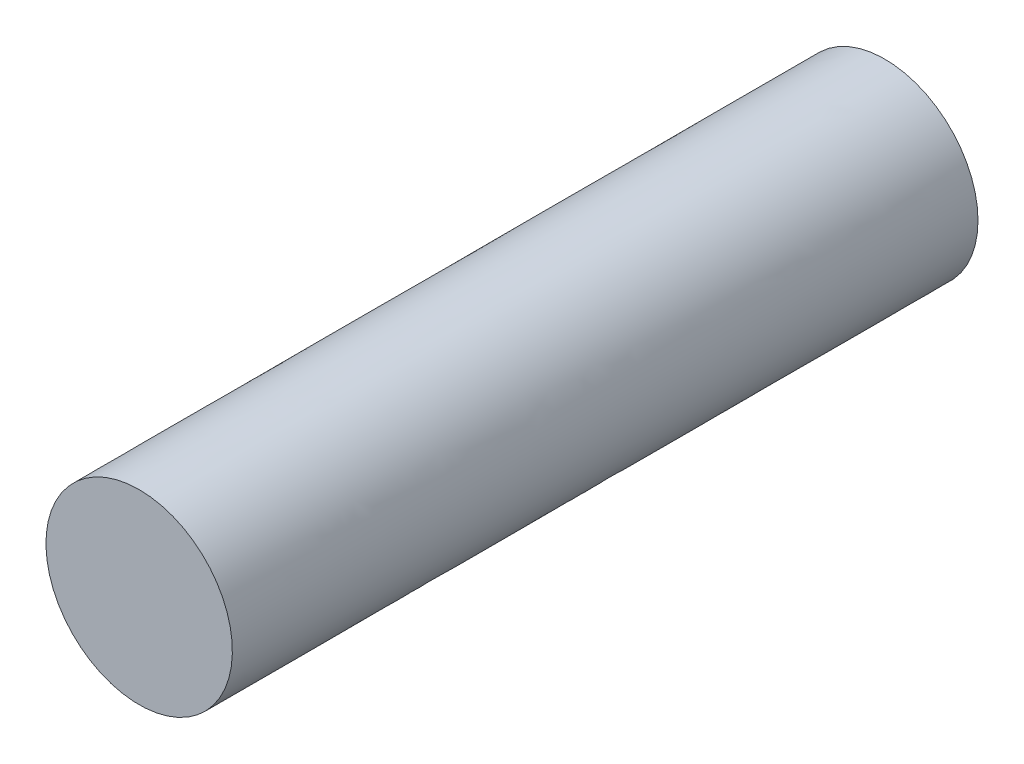
SolidWorks part; units mm, degrees
ref_plane "前视基准面" through (0, 0, 0) normal (0, 0, 1) x (1, 0, 0)
ref_plane "上视基准面" through (0, 0, 0) normal (0, 1, 0) x (1, 0, 0)
ref_plane "右视基准面" through (0, 0, 0) normal (1, 0, 0) x (0, 0, -1)
other "Configuration Table"
sketch "Profile1" plane through (0, 0, 0) normal (0, 0, 1) x (1, 0, 0)
  circle A0 centre (0, 0) radius 5
sketch "Path1" plane through (0, 0, 0) normal (1, 0, 0) x (0, 0, -1)
  line L0 (0, 0) -> (-40, 0)
sweep "sweep_twist90" add profiles "Profile1" path "Path1" parameters "D4"=90
